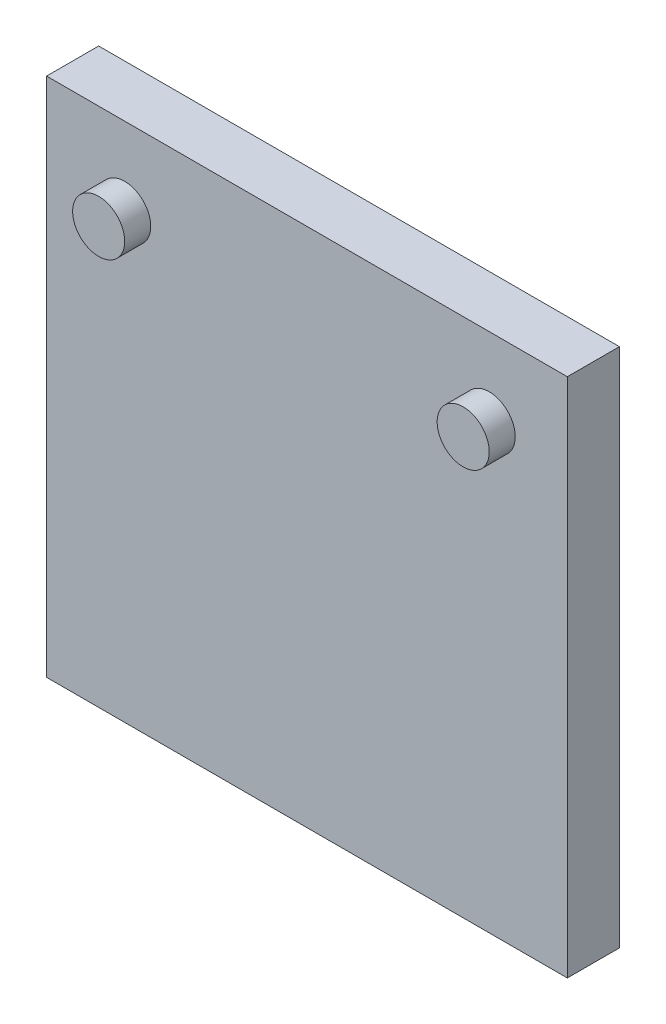
SolidWorks part; units mm, degrees
ref_plane "Front Plane" through (0, 0, 0) normal (0, 0, 1) x (1, 0, 0)
ref_plane "Top Plane" through (0, 0, 0) normal (0, 1, 0) x (1, 0, 0)
ref_plane "Right Plane" through (0, 0, 0) normal (1, 0, 0) x (0, 0, -1)
sketch "Sketch1" plane through (0, 0, 0) normal (0, 0, 1) x (1, 0, 0)
  line L1 (0, 0) -> (-100, 0)
  line L2 (0, 0) -> (0, 100)
  line L3 (0, 100) -> (-100, 100)
  line L4 (-100, 0) -> (-100, 100)
  dimension "D1" = 100
  dimension "D2" = 100
extrude "Boss-Extrude1" add sketch "Sketch1" along normal blind 10
sketch "Sketch2" plane through (0, 0, 10) normal (0, 0, 1) x (1, 0, 0)
  line L0 (0, 100) -> (-100, 100) construction
  line L1 (-100, 100) -> (-100, 0) construction
  line L2 (0, 0) -> (0, 100) construction
  circle A0 centre (-85, 85) radius 5
  circle A1 centre (-15, 85) radius 5
  dimension "D1" = 10
  dimension "D2" = 15
  dimension "D3" = 15
  dimension "D4" = 15
  dimension "D5" = 15
extrude "Boss-Extrude2" add sketch "Sketch2" along normal blind 5
